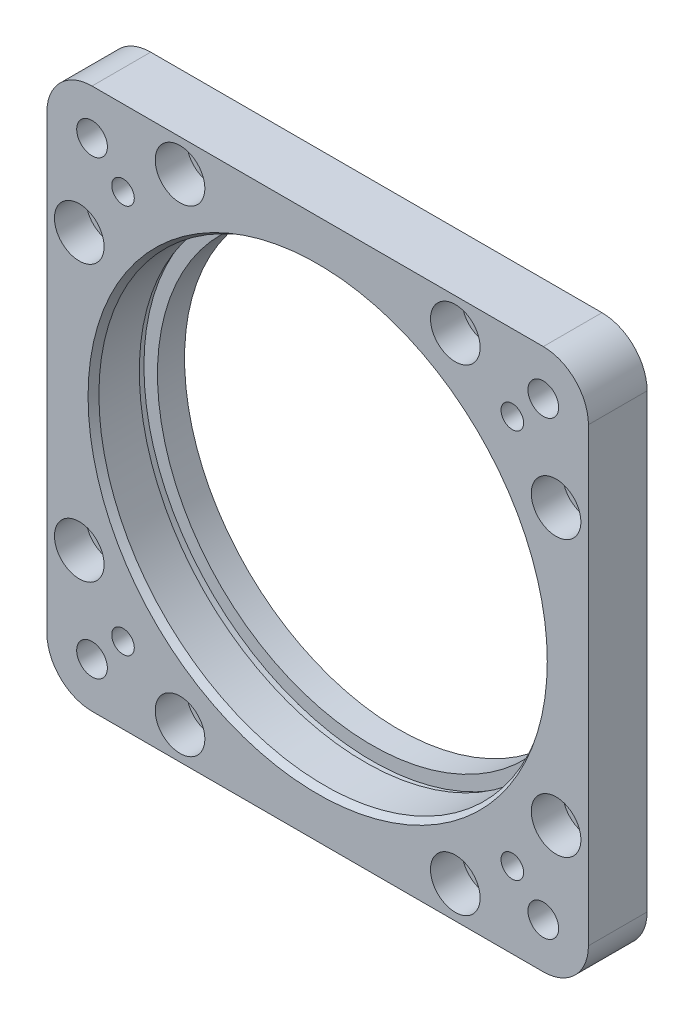
SolidWorks part; units mm, degrees
material "Low Carbon Steel"
ref_plane "Front Plane" through (0, 0, 0) normal (0, 0, 1) x (1, 0, 0)
ref_plane "Top Plane" through (0, 0, 0) normal (0, 1, 0) x (1, 0, 0)
ref_plane "Right Plane" through (0, 0, 0) normal (1, 0, 0) x (0, 0, -1)
sketch "Sketch1" plane through (0, 0, 0) normal (0, 0, 1) x (1, 0, 0)
  line L0 (-60, -60) -> (60, 60) construction
  line L1 (-60, -60) -> (60, -60)
  line L2 (-60, -60) -> (-60, 60)
  line L3 (-60, 60) -> (60, 60)
  line L4 (60, -60) -> (60, 60)
  circle A0 centre (0, 0) radius 47.5
  point P8 (0, 0)
  dimension "D2" = 95
  dimension "D1" = 120
extrude "Boss-Extrude1" add sketch "Sketch1" against normal blind 18
sketch "Sketch5" plane through (0, 0, -18) normal (0, 0, -1) x (-1, 0, 0)
  circle A0 centre (0, 0) radius 55
  dimension "D1" = 110
extrude "Cut-Extrude1" cut sketch "Sketch5" along direction (0, 0, -1) on the side against the normal blind 5 flip side to cut
sketch "Sketch12" plane through (0, 0, 0) normal (0, 0, 1) x (1, 0, 0)
  circle A0 centre (0, 0) radius 50
  dimension "D1" = 100
extrude "Cut-Extrude2" cut sketch "Sketch12" against normal blind 12
hole_wizard "CBORE for M6 Hex Socket Head Cap Screw1" positions "Sketch6" profile "Sketch7" counterbore size "M6" standard "Peddi DIN" end condition through all
sketch "Sketch6" plane through (0, 0, 0) normal (0, 0, 1) x (1, 0, 0)
  line L0 (0, 0) -> (-52.8275, 30.5) construction
  line L2 (0, 0) -> (-30.896, 0) construction
  line L4 (0, 25.6622) -> (0, 0) construction
  line L6 (0, 0) -> (-30.5, 52.8275) construction
  point P0 (-52.8275, 30.5)
  point P2 (-30.5, 52.8275)
  dimension "D1" = 61
  dimension "D2" = 30
  dimension "D3" = 30
sketch "Sketch7" plane through (-52.8275, 30.5, 0) normal (1, 0, 0) x (0, -1, 0)
  line L0 (0, 0) -> (0, 18)
  line L1 (0, 18) -> (3.3, 18)
  line L3 (3.3, 18) -> (3.3, 7)
  line L4 (3.3, 7) -> (5.5, 7)
  line L5 (5.5, 7) -> (5.5, 0)
  line L7 (5.5, 0) -> (0, 0)
  line L11 (0, -6.35) -> (0, 107.95) construction
  dimension "Thru Hole Dia." = 6.6
  dimension "Thru Hole Depth" = 18
  dimension "C'Bore Dia." = 11
  dimension "C'Bore Depth" = 7
pattern_circular "CirPattern1" count 4 every 90 about axis through (0, 0, 0) along (0, 0, 1) of "CBORE for M6 Hex Socket Head Cap Screw1"
fillet "Fillet1" radius 10 4 edges at (60, 60, -6.5) (60, -60, -6.5) (-60, -60, -6.5) (-60, 60, -6.5)
fillet "Fillet2" radius 0.38 1 edges at (-55, 0, -13)
chamfer "Chamfer1" distance 0.7 angle 45 1 edges at (-55, 0, -18)
hole_wizard "M6 Tapped Hole1" positions "Sketch8" profile "Sketch9" tap size "M6" standard "Peddi DIN" end condition through all
sketch "Sketch8" plane through (0, 0, 0) normal (0, 0, 1) x (1, 0, 0)
  line L0 (-43.1335, 43.1335) -> (43.1335, -43.1335) construction
  line L2 (43.1335, 43.1335) -> (-43.1335, -43.1335) construction
  line L4 (0, 0) -> (0, 32.9767) construction
  point P0 (-43.1335, -43.1335)
  point P2 (-43.1335, 43.1335)
  point P4 (43.1335, 43.1335)
  point P6 (43.1335, -43.1335)
  dimension "D1" = 122
  dimension "D2" = 45
sketch "Sketch9" plane through (-43.1335, -43.1335, 0) normal (1, 0, 0) x (0, -1, 0)
  line L0 (0, 0) -> (0, 18)
  line L1 (0, 18) -> (2.5, 18)
  line L2 (2.5, 18) -> (2.5, 0)
  line L5 (2.5, 0) -> (0, 0)
  line L11 (0, -6.35) -> (0, 107.95) construction
  dimension "Thru Tap Drill Dia." = 5
  dimension "Thru Tap Drill Depth" = 18
cosmetic thread "Hole Thread1" parameters "D2"=6
cosmetic thread "Hole Thread2" parameters "D2"=6
cosmetic thread "Hole Thread3" parameters "D2"=6
cosmetic thread "Hole Thread4" parameters "D2"=6
hole_wizard "M8 Tapped Hole1" positions "Sketch10" profile "Sketch11" tap size "M8" standard "Peddi DIN"
sketch "Sketch10" plane through (0, 0, 0) normal (0, 0, 1) x (1, 0, 0)
  line L0 (-50, 50) -> (50, 50) construction
  line L1 (-50, 50) -> (-50, -50) construction
  line L2 (50, 50) -> (50, -50) construction
  line L3 (-50, -50) -> (50, -50) construction
  line L5 (-50, 50) -> (50, -50) construction
  point P2 (-50, 50)
  point P3 (50, 50)
  point P77 (50, -50)
  point P78 (-50, -50)
  dimension "D1" = 100
sketch "Sketch11" plane through (-50, 50, 0) normal (1, 0, 0) x (0, -1, 0)
  line L0 (0, 0) -> (0, 35.0329)
  line L1 (0, 35.0329) -> (3.4, 32.99)
  line L2 (3.4, 32.99) -> (3.4, 0)
  line L5 (3.4, 0) -> (0, 0)
  line L10 (0, 35.0329) -> (-3.4, 32.99) construction
  line L11 (0, -6.35) -> (0, 107.95) construction
  dimension "Tap Drill Dia." = 6.8
  dimension "Tap Drill Depth" = 32.99
  dimension "Drill Angle" = 118
cosmetic thread "Hole Thread5" parameters "D1"=13, "D2"=8
cosmetic thread "Hole Thread6" parameters "D1"=13, "D2"=8
cosmetic thread "Hole Thread7" parameters "D1"=13, "D2"=8
cosmetic thread "Hole Thread8" parameters "D1"=13, "D2"=8
chamfer "Chamfer2" distance 1.524 angle 30 1 edges at (50, 0, 0)
sketch "Sketch13" plane through (0, 0, -12) normal (0, 0, 1) x (1, 0, 0)
  circle A0 centre (0, 0) radius 50.5
  dimension "D1" = 101
extrude "Cut-Extrude3" cut sketch "Sketch13" along normal blind 1.524
other "Freeze***"
